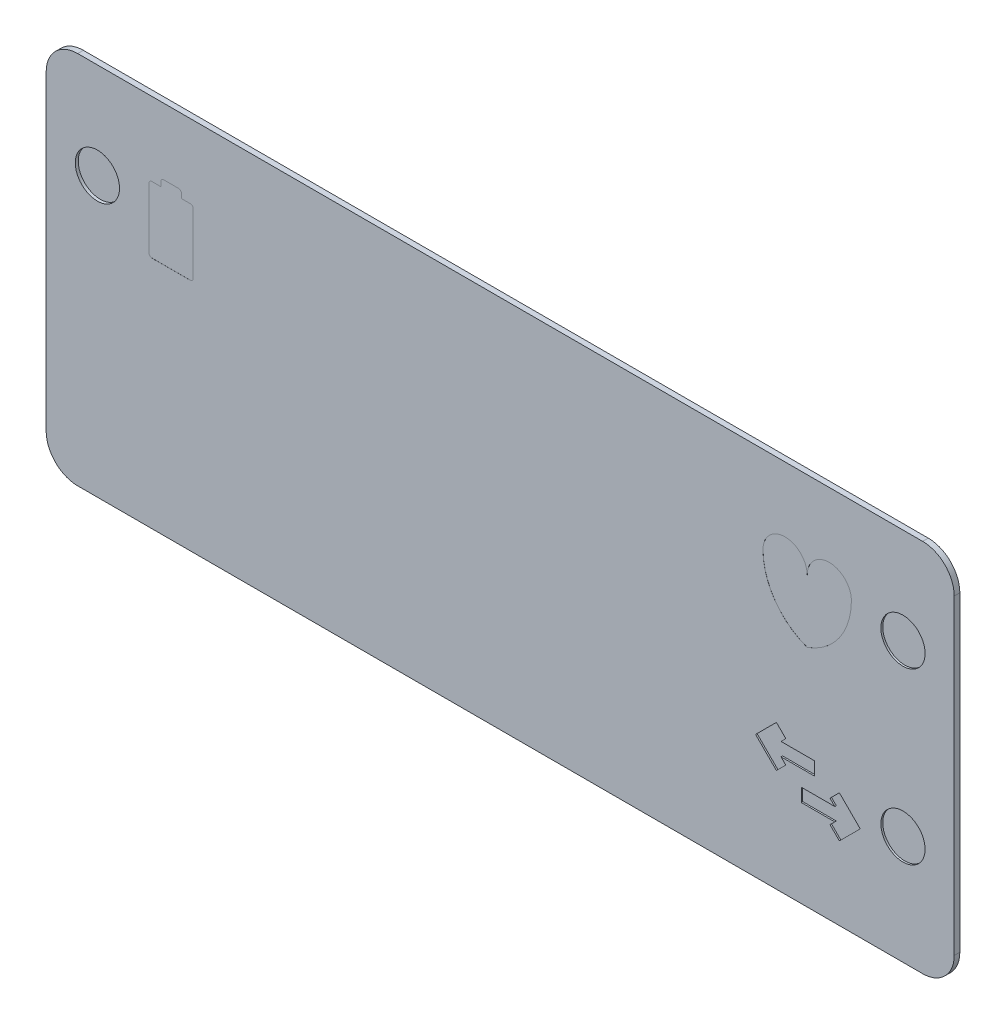
SolidWorks part; units mm, degrees
ref_plane "Front" through (0, 0, 0) normal (0, 0, 1) x (1, 0, 0)
ref_plane "Top" through (0, 0, 0) normal (0, 1, 0) x (1, 0, 0)
ref_plane "Right" through (0, 0, 0) normal (1, 0, 0) x (0, 0, -1)
sketch "Sketch1" plane through (0, 0, 0) normal (0, 0, 1) x (1, 0, 0)
  line L1 (2.14, 0) -> (59.46, 0)
  line L2 (0, 2.14) -> (0, 23.26)
  line L3 (2.14, 25.4) -> (59.46, 25.4)
  line L4 (61.6, 2.14) -> (61.6, 23.26)
  arc A0 (2.14, 0) -> (0, 2.14) centre (2.14, 2.14) cw
  arc A1 (59.46, 0) -> (61.6, 2.14) centre (59.46, 2.14) ccw
  arc A2 (61.6, 23.26) -> (59.46, 25.4) centre (59.46, 23.26) ccw
  arc A3 (2.14, 25.4) -> (0, 23.26) centre (2.14, 23.26) ccw
  point P7 (0, 0)
  point P12 (61.6, 25.4)
  point P15 (0, 25.4)
  dimension "D3" = 2.14
  dimension "D1" = 61.6
  dimension "D2" = 25.4
extrude "Boss-Extrude1" add sketch "Sketch1" along normal blind 0.381
sketch "Sketch2" plane through (0, 0, 0.381) normal (0, 0, 1) x (1, 0, 0)
  line L0 (30.8, 25.4) -> (30.8, 0) construction
  line L2 (2.14, 0) -> (59.46, 0) construction
  line L3 (58.125, 18.8976) -> (58.125, -4.1148) construction
  line L4 (3.475, 18.8976) -> (58.125, 18.8976) construction
  line L5 (48.5461, 7.3914) -> (55.3086, 7.3914) construction
  line L6 (3.475, 30.7351) -> (3.475, 17.3073) construction
  line L7 (59.46, 25.4) -> (2.14, 25.4) construction
  circle A1 centre (58.125, 18.8976) radius 1.5
  circle A2 centre (58.125, 7.3914) radius 1.5
  dimension "D1" = 3
  dimension "D2" = 27.325
  dimension "D3" = 7.3914
  dimension "D4" = 18.8976
  dimension "D5" = 27.325
extrude "Cut-Extrude1" cut sketch "Sketch2" against normal blind 0.127
sketch "Sketch17" plane through (0, 0, 0.381) normal (0, 0, 1) x (1, 0, 0)
  line L0 (30.8, 0) -> (30.8, 22.262) construction
  line L1 (2.14, 0) -> (59.46, 0) construction
  line L2 (58.125, 18.8976) -> (3.475, 18.8976) construction
  line L3 (3.475, 18.8976) -> (3.475, 16.2455) construction
  circle A0 centre (3.475, 18.8976) radius 1.5
  dimension "D2" = 3
  dimension "D1" = 27.325
extrude "Cut-Extrude9" cut sketch "Sketch17" against normal blind 0.2
sketch "Sketch10" plane through (0, 0, 0.381) normal (0, 0, 1) x (1, 0, 0)
  line L0 (51.625, 29.7824) -> (51.625, 19.4976) construction
  line L1 (40.6019, 17.9976) -> (41.1685, 17.9976) construction
  line L2 (43.0868, 17.9976) -> (43.716, 17.9976) construction
  line L3 (51.625, 29.2607) -> (51.625, 15.255) construction
  line L4 (50.125, 19.4976) -> (53.125, 19.4976) construction
  line L5 (48.7156, 18.8976) -> (48.207, 18.8976) construction
  line L6 (58.125, 18.8976) -> (58.125, 26.6614) construction
  arc A0 (51.625, 19.4976) -> (48.625, 19.4976) centre (50.125, 19.4976) ccw
  arc A1 (54.625, 19.4976) -> (51.625, 19.4976) centre (53.125, 19.4976) ccw
  arc A2 (48.625, 19.4976) -> (51.625, 15.255) centre (53.125, 19.4976) ccw
  arc A3 (54.625, 19.4976) -> (51.625, 15.255) centre (50.125, 19.4976) cw
  point P16 (51.625, 19.4976)
  dimension "D3" = 0.6
  dimension "D1" = 1.5
  dimension "D4" = 6.5
extrude "Heart Sym Cut-Extrude6" cut sketch "Sketch10" against normal blind 0.005
sketch "Sketch11" plane through (0, 0, 0.381) normal (0, 0, 1) x (1, 0, 0)
  line L0 (7.175, 20.3976) -> (7.775, 20.3976)
  line L1 (9.175, 20.3976) -> (9.775, 20.3976)
  line L2 (6.975, 20.1976) -> (6.975, 16.0976)
  line L3 (7.175, 15.8976) -> (9.775, 15.8976)
  line L4 (9.975, 20.1976) -> (9.975, 16.0976)
  line L5 (51.625, 15.255) -> (51.625, 14.7576) construction
  line L6 (7.775, 20.3976) -> (7.775, 20.6976)
  line L7 (7.975, 20.8976) -> (8.975, 20.8976)
  line L8 (9.175, 20.3976) -> (9.175, 20.6976)
  line L9 (8.475, 15.8976) -> (8.475, 20.8976) construction
  line L10 (3.475, 18.8976) -> (14.277, 18.8976) construction
  line L11 (8.475, 18.8976) -> (8.475, 24.0535) construction
  line L12 (6.975, 18.3976) -> (9.975, 18.3976) construction
  line L13 (3.475, 18.8976) -> (3.475, 18.4021) construction
  arc A0 (9.975, 16.0976) -> (9.775, 15.8976) centre (9.775, 16.0976) cw
  arc A1 (7.175, 15.8976) -> (6.975, 16.0976) centre (7.175, 16.0976) cw
  arc A2 (9.975, 20.1976) -> (9.775, 20.3976) centre (9.775, 20.1976) ccw
  arc A3 (6.975, 20.1976) -> (7.175, 20.3976) centre (7.175, 20.1976) cw
  arc A4 (9.175, 20.6976) -> (8.975, 20.8976) centre (8.975, 20.6976) ccw
  arc A5 (7.775, 20.6976) -> (7.975, 20.8976) centre (7.975, 20.6976) cw
  point P13 (8.475, 20.8976)
  point P32 (8.475, 18.3976)
  dimension "D1" = 0.2
  dimension "D2" = 0.2
  dimension "D3" = 0.5
  dimension "D4" = 5
  dimension "D5" = 3
  dimension "D7" = 1
  dimension "D8" = 0.5
extrude "Batt Sym Cut-Extrude7" cut sketch "Sketch11" against normal blind 0.005
sketch "Sketch12" plane through (0, 0, 0.381) normal (0, 0, 1) x (1, 0, 0)
  line L0 (50.8438, 7.6414) -> (50.1126, 8.3266)
  line L1 (50.1126, 8.3266) -> (50.4545, 8.6914)
  line L2 (50.4545, 8.6914) -> (51.8418, 7.3914)
  line L3 (51.8418, 7.3914) -> (50.4545, 6.0914)
  line L4 (50.8438, 7.1414) -> (49.3082, 7.1414)
  line L5 (49.3082, 7.1414) -> (49.3082, 7.6414)
  line L6 (49.3082, 7.6414) -> (50.8438, 7.6414)
  line L7 (50.8438, 7.1414) -> (50.1126, 6.4562)
  line L8 (50.1126, 6.4562) -> (50.4545, 6.0914)
  line L9 (52.3439, 8.3266) -> (53.3418, 7.3914)
  line L10 (49.3082, 7.3914) -> (54.9418, 7.3914) construction
  line L11 (52.6858, 6.0914) -> (53.8062, 7.1414)
  line L12 (52.3439, 8.3266) -> (52.6858, 8.6914)
  line L13 (52.6858, 8.6914) -> (53.8062, 7.6414)
  line L14 (52.3439, 6.4562) -> (39.6866, 6.4562) construction
  line L15 (52.3439, 6.4562) -> (52.6858, 6.0914)
  line L16 (53.8062, 7.1414) -> (54.9418, 7.1414)
  line L17 (54.9418, 7.1414) -> (54.9418, 7.6414)
  line L18 (54.9418, 7.6414) -> (53.8062, 7.6414)
  line L19 (52.3439, 6.4562) -> (53.3418, 7.3914)
  line L20 (52.6858, 6.0914) -> (42.4342, 6.0914) construction
  line L21 (52.6858, 8.6914) -> (41.7541, 8.6914) construction
  line L22 (58.125, 7.3914) -> (51.4424, 7.3914) construction
  line L23 (52.125, 7.3914) -> (52.125, 18.9676) construction
  line L24 (58.125, 7.3914) -> (58.125, 18.9676) construction
  line L25 (51.8418, 7.3914) -> (51.8418, 21.5786) construction
  line L26 (49.3082, 21.1893) -> (49.3082, 21.9616) construction
  line L27 (45.5349, 20.0944) -> (45.5349, 19.113) construction
  dimension "D1" = 0.5
  dimension "D2" = 0.5
  dimension "D3" = 0.5
  dimension "D4" = 1.3
  dimension "D5" = 1.3
  dimension "D6" = 1.5
  dimension "D7" = 1.6
  dimension "D8" = 6
  dimension "D9" = 1.5356
extrude "Cut-Extrude8" [suppressed] cut sketch "Sketch12" against normal blind 0.005
sketch "Sketch13" plane through (0, 0, 0.381) normal (0, 0, 1) x (1, 0, 0)
  line L0 (53.8108, 7.8056) -> (53.1744, 7.1692)
  line L1 (53.1744, 7.1692) -> (53.5022, 6.8414)
  line L2 (58.125, 7.3914) -> (42.91, 7.3914) construction
  line L3 (58.125, 7.3914) -> (58.125, 23.6089) construction
  line L11 (52.125, 8.3914) -> (48.125, 8.3914) construction
  line L12 (49.8478, 7.9414) -> (50.1756, 7.6136)
  line L13 (48.125, 8.3914) -> (49.5392, 6.9772)
  line L15 (51.225, 6.3914) -> (55.225, 6.3914) construction
  line L18 (51.225, 5.9414) -> (53.5022, 5.9414)
  line L19 (51.225, 6.8414) -> (51.225, 5.9414)
  line L20 (53.5022, 6.8414) -> (51.225, 6.8414)
  line L22 (55.225, 6.3914) -> (53.8108, 7.8056)
  line L23 (53.1744, 5.6136) -> (53.8108, 4.9772)
  line L25 (55.225, 6.3914) -> (53.8108, 4.9772)
  line L26 (53.5022, 5.9414) -> (53.1744, 5.6136)
  line L31 (50.1756, 7.6136) -> (49.5392, 6.9772)
  line L33 (48.125, 8.3914) -> (49.5392, 9.8056)
  line L34 (49.8478, 8.8414) -> (52.125, 8.8414)
  line L35 (52.125, 8.8414) -> (52.125, 7.9414)
  line L36 (52.125, 7.9414) -> (49.8478, 7.9414)
  line L37 (49.8478, 8.8414) -> (50.1756, 9.1692)
  line L38 (50.1756, 9.1692) -> (49.5392, 9.8056)
  point P15 (51.225, 6.3914)
  dimension "D2" = 0.9
  dimension "D3" = 1
  dimension "D4" = 6
  dimension "D5" = 1
  dimension "D6" = 45
  dimension "D7" = 45
  dimension "D8" = 0.9
  dimension "D9" = 2
  dimension "D10" = 0.9
  dimension "D12" = 45
  dimension "D14" = 2
  dimension "D16" = 4
  dimension "D17" = 4
extrude "Comm SymCut-Extrude9" cut sketch "Sketch13" against normal blind 0.1
sketch "Sketch16" plane through (0, 0, 0.381) normal (0, 0, 1) x (1, 0, 0)
  line L0 (72.8522, -45.5346) -> (327.5189, -45.5346) construction
